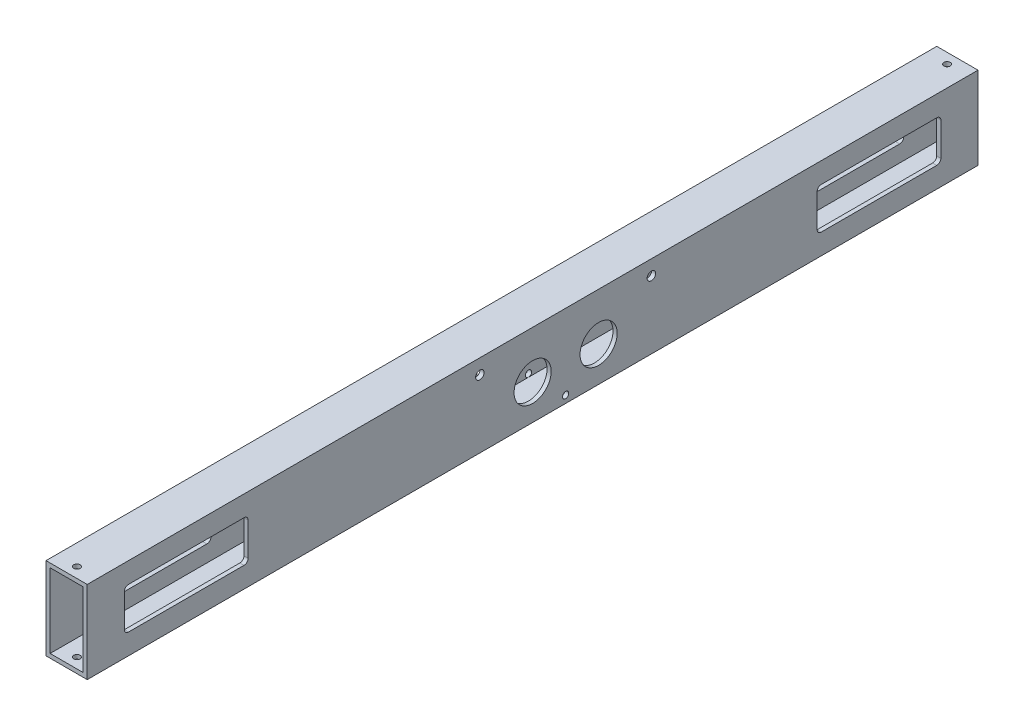
SolidWorks part; units mm, degrees
ref_plane "Front Plane" through (0, 0, 0) normal (0, 0, 1) x (1, 0, 0)
ref_plane "Top Plane" through (0, 0, 0) normal (0, 1, 0) x (1, 0, 0)
ref_plane "Right Plane" through (0, 0, 0) normal (1, 0, 0) x (0, 0, -1)
sketch "Sketch1" plane through (0, 0, 0) normal (0, 0, 1) x (1, 0, 0)
  line L1 (-12.1647, 2.5103) -> (19.5853, 2.5103)
  line L2 (-12.1647, 2.5103) -> (-12.1647, -60.9897)
  line L3 (-12.1647, -60.9897) -> (19.5853, -60.9897)
  line L4 (19.5853, 2.5103) -> (19.5853, -60.9897)
  line L5 (-8.9897, -0.6647) -> (16.4103, -0.6647)
  line L6 (-8.9897, -0.6647) -> (-8.9897, -57.8147)
  line L7 (-8.9897, -57.8147) -> (16.4103, -57.8147)
  line L8 (16.4103, -0.6647) -> (16.4103, -57.8147)
  dimension "D1" = 63.5
  dimension "D2" = 31.75
  dimension "D3" = 3.175
  dimension "D4" = 3.175
  dimension "D5" = 3.175
  dimension "D6" = 3.175
extrude "Boss-Extrude1" add sketch "Sketch1" along normal blind 685.8
sketch "Sketch3" plane through (-12.1647, 0, 0) normal (-1, 0, 0) x (0, 0, 1)
  line L0 (0, 2.5103) -> (0, -60.9897) construction
  line L1 (31.7754, -13.3647) -> (120.6754, -13.3647)
  line L2 (28.6004, -16.5397) -> (28.6004, -41.9397)
  line L3 (31.7754, -45.1147) -> (120.6754, -45.1147)
  line L4 (123.8504, -16.5397) -> (123.8504, -41.9397)
  line L5 (685.8, 2.5103) -> (0, 2.5103) construction
  line L6 (685.8, -60.9897) -> (0, -60.9897) construction
  line L7 (342.9, 2.5103) -> (342.9, -60.9897)
  line L8 (561.9496, -16.5397) -> (561.9496, -41.9397)
  line L9 (654.0246, -45.1147) -> (565.1246, -45.1147)
  line L10 (657.1996, -16.5397) -> (657.1996, -41.9397)
  line L11 (654.0246, -13.3647) -> (565.1246, -13.3647)
  arc A0 (28.6004, -41.9397) -> (31.7754, -45.1147) centre (31.7754, -41.9397) ccw
  arc A1 (120.6754, -45.1147) -> (123.8504, -41.9397) centre (120.6754, -41.9397) ccw
  arc A2 (120.6754, -13.3647) -> (123.8504, -16.5397) centre (120.6754, -16.5397) cw
  arc A3 (31.7754, -13.3647) -> (28.6004, -16.5397) centre (31.7754, -16.5397) ccw
  arc A4 (654.0246, -13.3647) -> (657.1996, -16.5397) centre (654.0246, -16.5397) cw
  arc A5 (565.1246, -13.3647) -> (561.9496, -16.5397) centre (565.1246, -16.5397) ccw
  arc A6 (565.1246, -45.1147) -> (561.9496, -41.9397) centre (565.1246, -41.9397) cw
  arc A7 (657.1996, -41.9397) -> (654.0246, -45.1147) centre (654.0246, -41.9397) cw
  dimension "D5" = 3.175
  dimension "D1" = 28.6004
  dimension "D2" = 15.875
  dimension "D3" = 15.875
  dimension "D4" = 95.25
extrude "Cut-Extrude1" cut sketch "Sketch3" against normal up to surface (31.75 mm away) contours L1 A3 L2 A0 L3 A1 L4 A2 | A7 L10 A4 L11 A5 L8 A6 L9 up to face at (19.5853, -29.2397, 342.9)
sketch "Sketch4" plane through (0, 2.5103, 0) normal (0, 1, 0) x (1, 0, 0)
  line L0 (19.5853, -685.8) -> (-12.1647, -685.8) construction
  line L1 (19.5853, 0) -> (-12.1647, 0) construction
  point P0 (3.7103, -677.8625)
  point P3 (3.7103, -685.8)
  point P4 (3.7103, -7.9375)
  dimension "D1" = 7.9375
  dimension "D2" = 7.9375
hole_wizard "#10 (0.1935) Diameter Hole1" positions "3DSketch1" profile "Sketch5" hole size "#10" standard "ANSI Inch" end condition through all
sketch3d "3DSketch1"
  point P0 (3.7103, 2.5103, 677.8625)
  point P3 (3.7103, 2.5103, 7.9375)
sketch "Sketch5" plane through (3.7103, 2.5103, 677.8625) normal (1, 0, 0) x (0, 0, 1)
  line L0 (0, 0) -> (0, 63.5)
  line L1 (0, 63.5) -> (2.4574, 63.5)
  line L2 (2.4574, 63.5) -> (2.4574, 0)
  line L5 (2.4574, 0) -> (0, 0)
  line L11 (0, -6.35) -> (0, 107.95) construction
  dimension "Thru Hole Dia." = 4.9149
  dimension "Thru Hole Depth" = 63.5
sketch "Sketch6" plane through (19.5853, 0, 0) normal (1, 0, 0) x (0, 0, -1)
  line L0 (-685.8, -60.9897) -> (0, -60.9897) construction
  line L4 (-685.8, -60.9897) -> (-685.8, 2.5103) construction
  circle A0 centre (-342.9, -34.0022) radius 14.2875
  circle A1 centre (-383.54, -8.9197) radius 3.2639
  circle A2 centre (-251.46, -8.9197) radius 3.2639
  circle A3 centre (-317.5, -55.4017) radius 2.413
  circle A4 centre (-292.1, -34.0022) radius 14.2875
  point P10 (-342.9, -60.9897)
  dimension "D1" = 28.575
  dimension "D4" = 6.5278
  dimension "D6" = 6.5278
  dimension "D8" = 4.826
  dimension "D14" = 28.575
  dimension "D2" = 26.9875
  dimension "D3" = 342.9
  dimension "D5" = 40.64
  dimension "D7" = 91.44
  dimension "D9" = 5.588
  dimension "D10" = 25.4
  dimension "D11" = 52.07
  dimension "D12" = 52.07
  dimension "D13" = 50.8
  dimension "D15" = 0
extrude "Cut-Extrude2" cut sketch "Sketch6" against normal up to surface (31.75 mm away)
